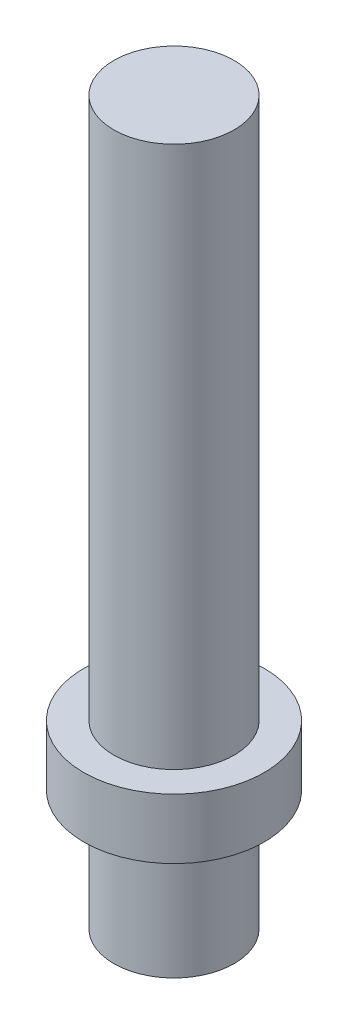
SolidWorks part; units mm, degrees
ref_plane "Front Plane" through (0, 0, 0) normal (0, 0, 1) x (1, 0, 0)
ref_plane "Top Plane" through (0, 0, 0) normal (0, 1, 0) x (1, 0, 0)
ref_plane "Right Plane" through (0, 0, 0) normal (1, 0, 0) x (0, 0, -1)
sketch "Sketch1" plane through (0, 0, 0) normal (0, 1, 0) x (1, 0, 0)
  circle A0 centre (0, 0) radius 1.5875
  dimension "D1" = 3.175
extrude "Boss-Extrude1" add sketch "Sketch1" along normal blind 3.175
sketch "Sketch2" plane through (0, 3.175, 0) normal (0, 1, 0) x (1, 0, 0)
  circle A0 centre (0, 0) radius 2.3813
  dimension "D1" = 4.7625
extrude "Boss-Extrude2" add sketch "Sketch2" along normal blind 1.5875
sketch "Sketch3" plane through (0, 4.7625, 0) normal (0, 1, 0) x (1, 0, 0)
  circle A0 centre (0, 0) radius 1.5875
  dimension "D1" = 3.175
extrude "Boss-Extrude3" add sketch "Sketch3" along normal blind 14.2875
